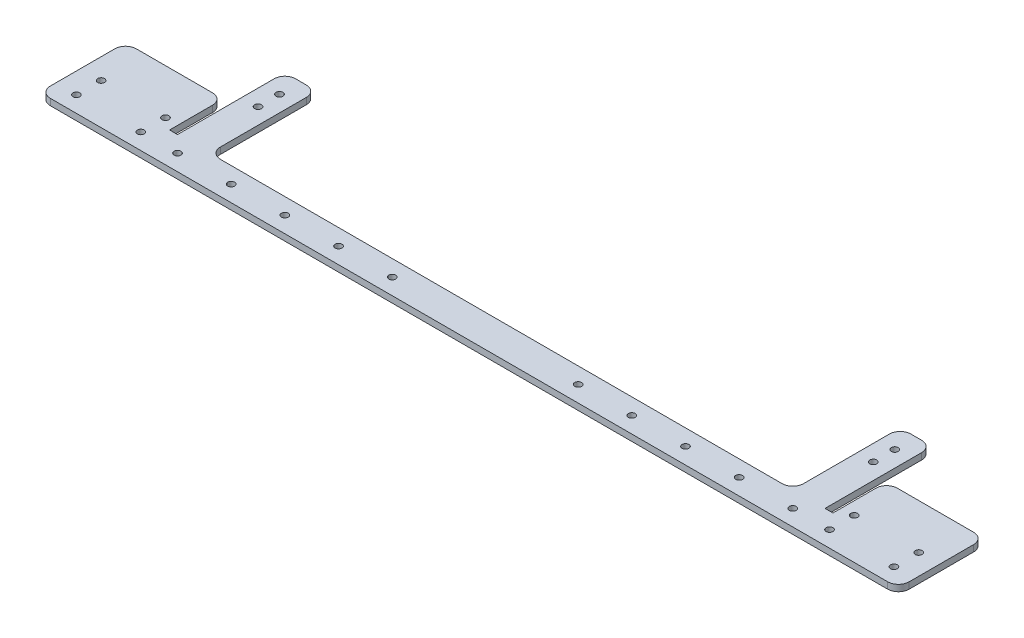
SolidWorks part; units mm, degrees
ref_plane "Front Plane" through (0, 0, 0) normal (0, 0, 1) x (1, 0, 0)
ref_plane "Top Plane" through (0, 0, 0) normal (0, 1, 0) x (1, 0, 0)
ref_plane "Right Plane" through (0, 0, 0) normal (1, 0, 0) x (0, 0, -1)
sketch "Sketch1" plane through (0, 0, 0) normal (0, 1, 0) x (1, 0, 0)
  line L0 (49.2, 15) -> (49.2, 0) construction
  line L1 (0, 0) -> (400, 0)
  line L2 (0, 0) -> (0, 15)
  line L3 (0, 15) -> (400, 15)
  line L4 (400, 0) -> (400, 15)
  line L5 (9.6, 19) -> (9.6, -4) construction
  line L6 (49.2, 15) -> (64.2, 15)
  line L7 (49.2, 15) -> (49.2, 65)
  line L8 (49.2, 65) -> (64.2, 65)
  line L9 (64.2, 15) -> (64.2, 65)
  line L10 (0, -15) -> (49.2, -15)
  line L11 (0, -15) -> (0, 30)
  line L12 (0, 30) -> (49.2, 30)
  line L13 (49.2, -15) -> (49.2, 30)
  line L14 (56.7, 65) -> (56.7, 0) construction
  line L15 (24.6, 30) -> (24.6, -15) construction
  line L16 (9.6, 7.5) -> (56.7, 7.5) construction
  line L17 (200, 15) -> (200, 0) construction
  line L18 (350.8, 65) -> (335.8, 65)
  line L19 (335.8, 15) -> (335.8, 65)
  line L20 (350.8, 15) -> (335.8, 15)
  line L21 (350.8, 15) -> (350.8, 65)
  line L22 (400, 30) -> (350.8, 30)
  line L23 (350.8, -15) -> (350.8, 30)
  line L24 (400, -15) -> (350.8, -15)
  line L25 (400, -15) -> (400, 30)
  circle A0 centre (9.6, 19) radius 1.6
  circle A1 centre (9.6, -4) radius 1.6
  circle A2 centre (39.6, -4) radius 1.6
  circle A3 centre (39.6, 19) radius 1.6
  circle A4 centre (56.7, 55) radius 1.6
  circle A5 centre (56.7, 45) radius 1.6
  circle A6 centre (56.7, 7.5) radius 1.6
  circle A7 centre (9.6, 7.5) radius 1.6
  circle A8 centre (81.7, 7.5) radius 1.6
  circle A9 centre (106.7, 7.5) radius 1.6
  circle A10 centre (131.7, 7.5) radius 1.6
  circle A11 centre (39.6, 7.5) radius 1.6
  circle A12 centre (268.3, 7.5) radius 1.6
  circle A13 centre (293.3, 7.5) radius 1.6
  circle A14 centre (318.3, 7.5) radius 1.6
  circle A15 centre (343.3, 7.5) radius 1.6
  circle A16 centre (343.3, 45) radius 1.6
  circle A17 centre (343.3, 55) radius 1.6
  circle A18 centre (360.4, -4) radius 1.6
  circle A19 centre (360.4, 7.5) radius 1.6
  circle A20 centre (360.4, 19) radius 1.6
  circle A21 centre (390.4, -4) radius 1.6
  circle A22 centre (390.4, 7.5) radius 1.6
  circle A23 centre (390.4, 19) radius 1.6
  circle A24 centre (156.7, 7.5) radius 1.6
  circle A25 centre (243.3, 7.5) radius 1.6
  dimension "D7" = 3.2
  dimension "D9" = 4
  dimension "D10" = 4
  dimension "D11" = 10
  dimension "D12" = 10
  dimension "D13" = 25
  dimension "D14" = 25
  dimension "D15" = 25
  dimension "D16" = 25
  dimension "D1" = 400
  dimension "D2" = 15
  dimension "D3" = 49.2
  dimension "D4" = 15
  dimension "D5" = 15
  dimension "D6" = 50
  dimension "D8" = 15
extrude "Boss-Extrude1" add sketch "Sketch1" along normal blind 3 contours L12 L11 L3 L7 A0 A3 | L1 L13 L3 L2 A7 A11 | L10 L13 L1 L11 A1 A2 | L3 L9 L8 L7 A5 A4 | L1 L23 L3 L13 A14 A12 A10 A9 A8 A6 A13 A15 | L3 L21 L18 L19 A16 A17 | L3 L25 L22 L21 A20 A23 | L23 L1 L4 L3 A19 A22 | L24 L25 L1 L23 A18 A21
fillet "Fillet1" radius 5 10 edges at (400, 1.5, 15) (350.8, 1.5, 15) (49.2, 1.5, 15) (0, 1.5, 15) (49.2, 1.5, -65) (64.2, 1.5, -65) (64.2, 1.5, -15) (335.8, 1.5, -15) (335.8, 1.5, -65) (350.8, 1.5, -65)
sketch "Sketch2" plane through (0, 3, 0) normal (0, 1, 0) x (1, 0, 0)
  line L0 (400, -10) -> (400, 30) construction
  line L1 (0, 0) -> (400, 0)
  line L2 (0, 0) -> (0, -15)
  line L3 (0, -15) -> (400, -15)
  line L4 (400, 0) -> (400, -15)
  line L7 (395, -15) -> (355.8, -15) construction
extrude "Cut-Extrude1" cut sketch "Sketch2" against normal through all
fillet "Fillet2" radius 5 2 edges at (0, 1.5, 0) (400, 1.5, 0)
sketch "Sketch3" plane through (0, 0, 0) normal (0, -1, 0) x (1, 0, 0)
  line L1 (400, -30) -> (354.5, -30)
  line L2 (400, -30) -> (400, -40)
  line L3 (400, -40) -> (354.5, -40)
  line L4 (354.5, -30) -> (354.5, -40)
  line L5 (0, -30) -> (45.5, -30)
  line L6 (0, -30) -> (0, -40)
  line L7 (0, -40) -> (45.5, -40)
  line L8 (45.5, -30) -> (45.5, -40)
  dimension "D1" = 45.5
  dimension "D2" = 10
  dimension "D3" = 10
  dimension "D4" = 45.5
extrude "Boss-Extrude2" add sketch "Sketch3" against normal blind 3
fillet "Fillet3" radius 5 4 edges at (354.5, 1.5, -40) (400, 1.5, -40) (0, 1.5, -40) (45.5, 1.5, -40)
sketch "Sketch4" plane through (0, 3, 0) normal (0, 1, 0) x (1, 0, 0)
  line L0 (354.5, 30) -> (354.5, 35) construction
  line L1 (354.5, 30) -> (350.8, 30)
  line L2 (354.5, 30) -> (354.5, 15)
  line L3 (354.5, 15) -> (350.8, 15)
  line L4 (350.8, 30) -> (350.8, 15)
  line L5 (354.5, 30) -> (350.8, 30) construction
  line L6 (49.2, 30) -> (49.2, 60) construction
  line L7 (49.2, 30) -> (45.5, 30)
  line L8 (49.2, 30) -> (49.2, 15)
  line L9 (49.2, 15) -> (45.5, 15)
  line L10 (45.5, 30) -> (45.5, 15)
  line L11 (45.5, 30) -> (49.2, 30) construction
  line L12 (45.5, 35) -> (45.5, 30) construction
  line L13 (350.8, 30) -> (350.8, 60) construction
  dimension "D1" = 15
  dimension "D2" = 15
extrude "Cut-Extrude2" cut sketch "Sketch4" against normal through all
